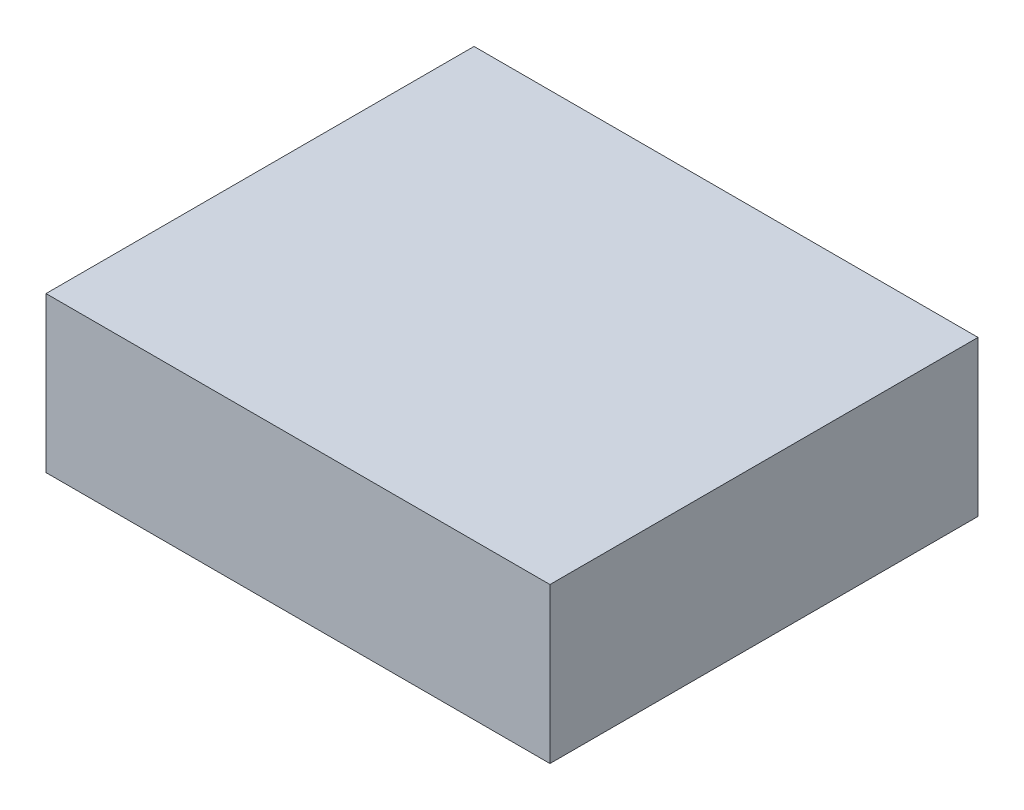
SolidWorks part; units mm, degrees
ref_plane "Front Plane" through (0, 0, 0) normal (0, 0, 1) x (1, 0, 0)
ref_plane "Top Plane" through (0, 0, 0) normal (0, 1, 0) x (1, 0, 0)
ref_plane "Right Plane" through (0, 0, 0) normal (1, 0, 0) x (0, 0, -1)
sketch "Sketch1" plane through (0, 0, 0) normal (0, 1, 0) x (1, 0, 0)
  line L1 (-156, -132.5) -> (156, -132.5)
  line L2 (-156, -132.5) -> (-156, 132.5)
  line L3 (-156, 132.5) -> (156, 132.5)
  line L4 (156, -132.5) -> (156, 132.5)
  line L5 (-156, -132.5) -> (156, 132.5) construction
  line L6 (-156, 132.5) -> (156, -132.5) construction
  point P0 (0, 0)
  dimension "D1" = 312
  dimension "D2" = 265
extrude "Boss-Extrude1" add sketch "Sketch1" along normal blind 96
sketch "Top_view" plane through (0, 0, 0) normal (0, 1, 0) x (1, 0, 0)
  line L0 (-36.2924, 118.7403) -> (700.3743, 118.7403) construction
  line L2 (46.2168, 3.6514) -> (872.8835, 3.6514) construction
  line L3 (46.577, 368) -> (873.2436, 368) construction
  point P2 (0, 0)
  point P9 (0, -5.5649)
  point P10 (0, -196.116)
  point P13 (0, 0)
  point P15 (159.8436, -10.2385)
sketch "Side_view" plane through (0, 0, 0) normal (1, 0, 0) x (0, 0, -1)
  line L0 (34.1822, 191.7039) -> (834.1822, 191.7039) construction
sketch "Front_view" plane through (0, 0, 0) normal (0, 0, 1) x (1, 0, 0)
  line L0 (43, -12.3945) -> (843, -12.3945) construction
sketch "Fuselage_sections" plane through (0, 0, 0) normal (0, 0, 1) x (1, 0, 0)
  line L0 (-106.4265, 35.7167) -> (632.9068, 35.7167) construction
sketch "Fuselage_side_profile" plane through (0, 0, 0) normal (1, 0, 0) x (0, 0, -1)
  line L0 (49.2408, -371.1026) -> (788.5741, -371.1026) construction
  line L1 (-46.7241, 61.5324) -> (-35.061, 68.3904)
  line L2 (128.0261, 89.4136) -> (132.5, 54.8689)
  line L3 (132.5, 96) -> (132.5, 0) construction
  line L4 (119.3999, 47.8759) -> (123.4698, 48.505)
  line L5 (118.3263, 46.7325) -> (118.1423, 41.3524)
  spline S0 degree 3 poles (-132.5, 43.723) (-132.0961, 33.6815) (-81.3219, 24.1586) (40.5978, 32.428) knots 0 0 0 0 1 1 1 1
  spline S1 degree 3 poles (-132.5, 43.723) (-132.5547, 52.1907) (-87.7432, 59.5774) (-46.7241, 61.5324) knots 0 0 0 0 1 1 1 1
  spline S2 degree 3 poles (-35.061, 68.3904) (-27.6346, 72.7572) (-10.4965, 69.6117) (16.5942, 59.8813) knots 0 0 0 0 1 1 1 1
  spline S3 degree 3 poles (16.5942, 59.8813) (56.1796, 56.5789) (68.2826, 55.0531) (73.5505, 55.7116) knots 0 0 0 0 1 1 1 1
  spline S4 degree 3 poles (73.5505, 55.7116) (75.2179, 56.1881) (100.0697, 82.1458) (115.6214, 97.7144) (127.1646, 96.0653) (128.0261, 89.4136) knots 0 0 0 0 1.107688 1.307688 2 2 2 2
  spline S5 degree 3 poles (123.4698, 48.505) (123.8548, 50.3178) (132.7152, 53.2069) (132.5, 54.8689) knots 0 0 0 0 1 1 1 1
  spline S6 degree 1 poles (40.5978, 32.428) (118.1423, 41.3524) knots 0 0 1 1
  spline S7 degree 3 poles (118.3263, 46.7325) (118.3794, 47.4233) (118.7451, 47.7747) (119.3999, 47.8759) knots 0 0 0 0 1 1 1 1
  point P24 (-132.5, 43.723)
ref_plane "Plane1" through (0, 43.723, 0) normal (0, 1, 0) x (1, 0, 0)
sketch "Fuselage_top_profile" plane through (0, 0, 0) normal (0, 1, 0) x (1, 0, 0)
  line L0 (0, -132.5) -> (0, 40.5978) construction
  line L1 (0, -132.5) -> (0, -46.7241) construction
  line L2 (0, 123.4698) -> (0, 132.5039) construction
  spline S0 degree 3 poles (0, -132.5) (1.348, -132.3811) (3.6062, -130.4798) (5.304, -125.861) knots 0 0 0 0 1 1 1 1
  spline S1 degree 3 poles (5.304, -125.861) (9.0049, -116.0028) (12.0965, -105.6468) (14.5788, -94.7929) knots 0 0 0 0 1 1 1 1
  spline S2 degree 3 poles (14.5788, -94.7929) (21.4928, -64.5604) (21.2462, -59.1858) (20.9791, -46.5189) knots 0 0 0 0 1 1 1 1
  spline S3 degree 3 poles (20.9791, -46.5189) (21.6944, 4.6054) (17.7568, 32.7271) (9.3699, 73.8624) knots 0 0 0 0 1 1 1 1
  spline S4 degree 2 poles (0, 132.5039) (6.0371, 90.2089) (9.3699, 73.8624) knots 0 0 0 1 1 1
sketch3d "3DSketch1"
  point P0 (-22.9675, 34.5945, 57.0298)
  point P1 (-152.4367, 48.351, 11.4687)
  point P2 (-22.2981, 34.5646, 0)
  point P3 (-22.2981, 34.5945, 0)
  point P4 (-151.7621, 48.351, 0)
  point P5 (-22.9675, 34.5945, 57.0298)
  point P6 (-152.4367, 48.351, 11.4687)
sketch3d "3DSketch2"
  circle A0 centre (-56.2252, 24.8249, 83.499) radius 5.9519
  point P0 (-56.2252, 24.8249, 83.499)
  point P1 (57.1499, 24.8446, 84.175)
  point P2 (57.1499, 24.6433, 83.4908)
  point P3 (57.1499, 24.8308, 83.4908)
  point P6 (-56.2252, 24.8249, 89.4509)
  point P7 (-56.8122, 24.8308, 83.4908)
  point P8 (-56.2252, 25.3561, 83.4908)
  point P9 (-56.2252, 24.6853, 83.3949)
  point P10 (-56.2252, 24.8249, 83.499)
